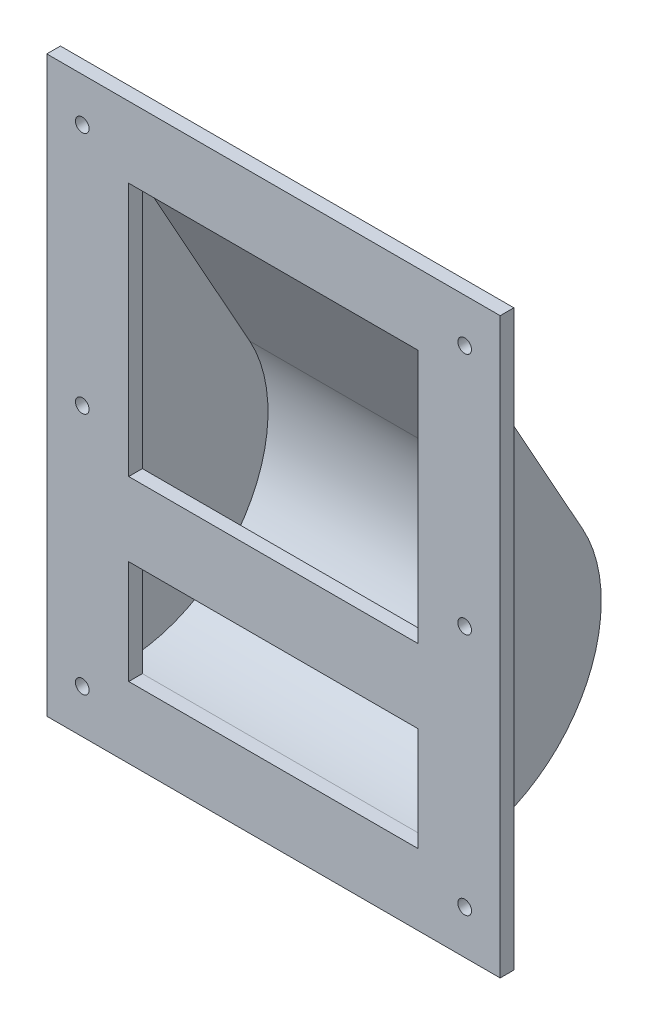
SolidWorks part; units mm, degrees
material "ABS"
ref_plane "Plan de face" through (0, 0, 0) normal (0, 0, 1) x (1, 0, 0)
ref_plane "Plan de dessus" through (0, 0, 0) normal (0, 1, 0) x (1, 0, 0)
ref_plane "Plan de droite" through (0, 0, 0) normal (1, 0, 0) x (0, 0, -1)
sketch "Esquisse1" plane through (0, 0, 0) normal (1, 0, 0) x (0, 0, -1)
  line L0 (47.1792, 26.2703) -> (0, 111)
  line L1 (0, 111) -> (0, 0) construction
  arc A0 (0, -54) -> (47.1792, 26.2703) centre (0, 0) ccw
  dimension "D1" = 165
  dimension "D2" = 54
extrude "Extru.-Mince1" add sketch "Esquisse1" along normal mid plane 120 thin thin type one direction reverse wall 1
sketch "Esquisse2" plane through (60, 0, 0) normal (1, 0, 0) x (0, 0, -1)
  line L0 (0, 111) -> (0, -54)
  line L2 (47.1792, 26.2703) -> (0, 111) construction
  line L3 (47.1792, 26.2703) -> (0, 111)
  arc A0 (0, -54) -> (47.1792, 26.2703) centre (0, 0) ccw construction
  arc A1 (0, -54) -> (47.1792, 26.2703) centre (0, 0) ccw
extrude "Boss.-Extru.1" add sketch "Esquisse2" along normal blind 1
sketch "Esquisse3" plane through (-60, 0, 0) normal (-1, 0, 0) x (0, 0, 1)
  line L0 (0, 111) -> (0, -54)
  line L1 (-47.1792, 26.2703) -> (0, 111) construction
  line L2 (-47.1792, 26.2703) -> (0, 111)
  arc A0 (-47.1792, 26.2703) -> (0, -54) centre (0, 0) ccw construction
  arc A1 (-47.1792, 26.2703) -> (0, -54) centre (0, 0) ccw
extrude "Boss.-Extru.2" add sketch "Esquisse3" along normal blind 1
sketch "Esquisse4" plane through (0, 0, 0) normal (0, 0, 1) x (1, 0, 0)
  line L0 (0, 0) -> (0, -79) construction
  line L1 (-83, 131) -> (83, 131)
  line L2 (-83, 131) -> (-83, -79)
  line L3 (-83, -79) -> (83, -79)
  line L4 (83, 131) -> (83, -79)
  line L5 (61, -54) -> (-61, -54) construction
  line L7 (-53, 105) -> (53, 105)
  line L8 (-53, 105) -> (-53, 12)
  line L9 (-53, 12) -> (53, 12)
  line L10 (53, 105) -> (53, 12)
  line L11 (-53, -15) -> (53, -15)
  line L12 (-53, -15) -> (-53, -53)
  line L13 (-53, -53) -> (53, -53)
  line L14 (53, -15) -> (53, -53)
  point P17 (0, -53)
  dimension "D1" = 166
  dimension "D2" = 210
  dimension "D3" = 25
  dimension "D4" = 26
  dimension "D5" = 26
  dimension "D6" = 30
  dimension "D7" = 93
  dimension "D8" = 38
  dimension "D9" = 27
extrude "Boss.-Extru.3" add sketch "Esquisse4" along normal blind 5
sketch "Esquisse5" plane through (0, 0, 5) normal (0, 0, 1) x (1, 0, 0)
  line L0 (0, 0) -> (0, 81.1776) construction
  line L1 (-83, -79) -> (83, -79) construction
  line L2 (-83, 131) -> (-83, -79) construction
  circle A0 centre (-70, 115) radius 2.5
  circle A1 centre (-70, 26) radius 2.5
  circle A2 centre (-70, -63) radius 2.5
  circle A3 centre (70, -63) radius 2.5
  circle A4 centre (70, 26) radius 2.5
  circle A5 centre (70, 115) radius 2.5
  dimension "D1" = 16
  dimension "D4" = 13
  dimension "D5" = 5
  dimension "D2" = 105
  dimension "D3" = 194
extrude "Enlèv. mat.-Extru.1" cut sketch "Esquisse5" against normal through all
